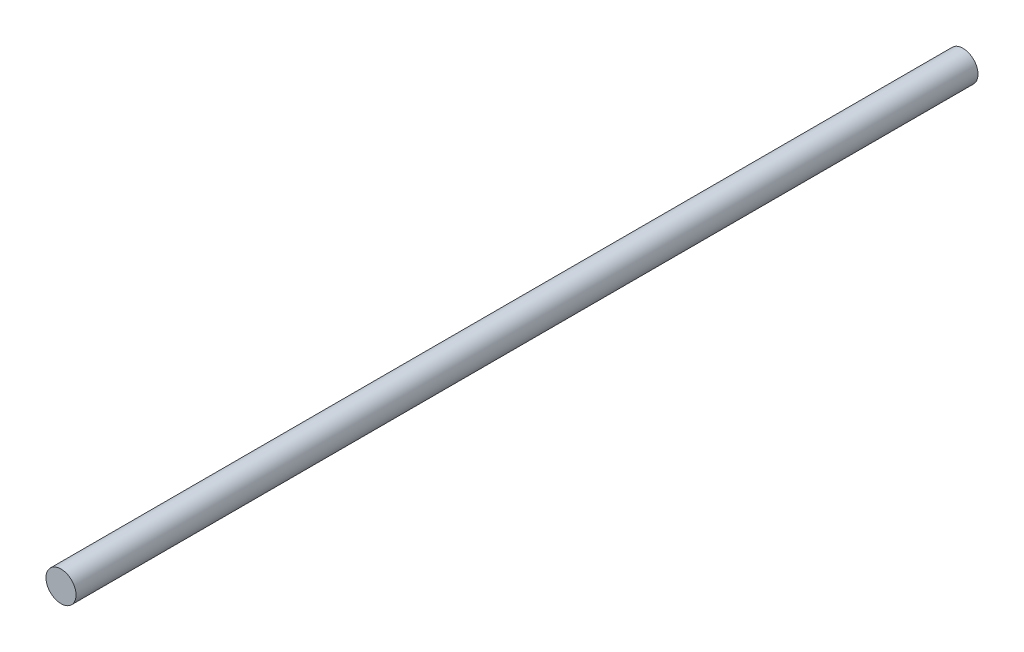
SolidWorks part; units mm, degrees
ref_plane "正面" through (0, 0, 0) normal (0, 0, 1) x (1, 0, 0)
ref_plane "平面" through (0, 0, 0) normal (0, 1, 0) x (1, 0, 0)
ref_plane "右側面" through (0, 0, 0) normal (1, 0, 0) x (0, 0, -1)
sketch "ｽｹｯﾁ1" plane through (0, 0, 0) normal (0, 0, 1) x (1, 0, 0)
  circle A0 centre (0, 0) radius 1
  dimension "D1" = 2
extrude "ﾎﾞｽ - 押し出し1" add sketch "ｽｹｯﾁ1" along normal blind 60
